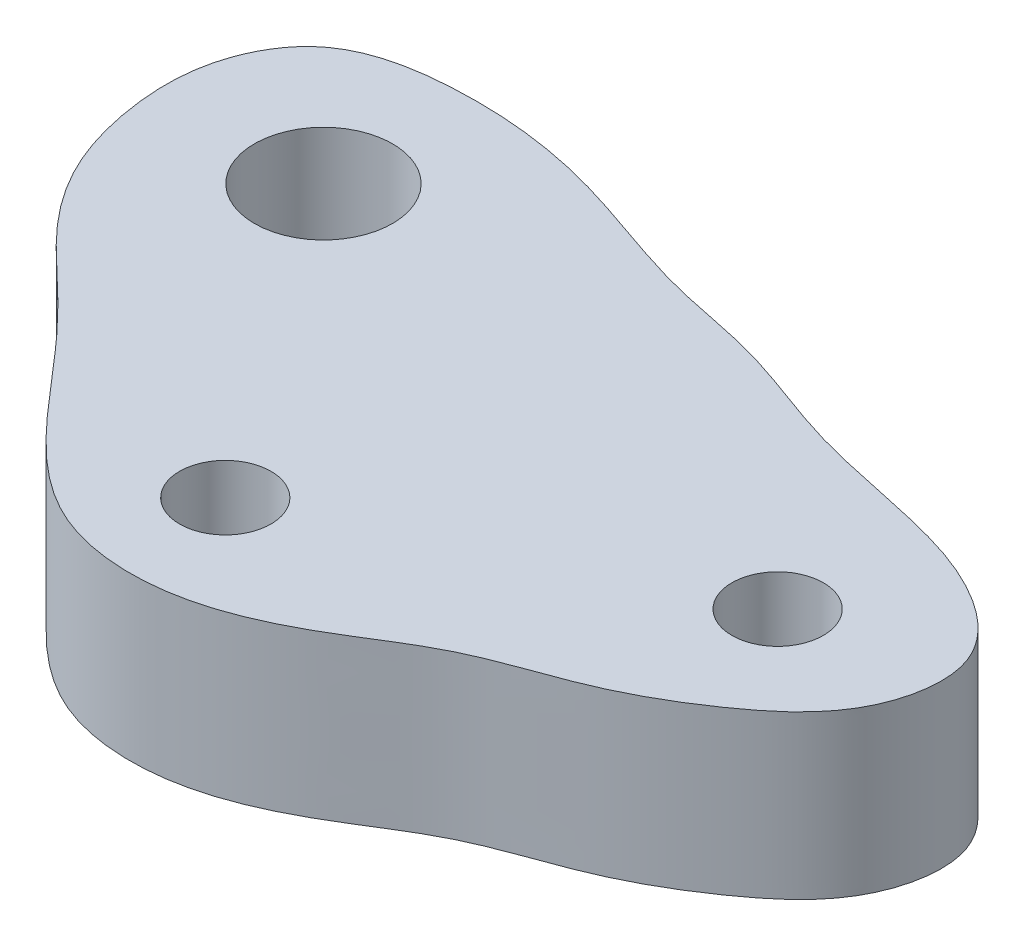
SolidWorks part; units mm, degrees
ref_plane "Front Plane" through (0, 0, 0) normal (0, 0, 1) x (1, 0, 0)
ref_plane "Top Plane" through (0, 0, 0) normal (0, 1, 0) x (1, 0, 0)
ref_plane "Right Plane" through (0, 0, 0) normal (1, 0, 0) x (0, 0, -1)
sketch "Sketch1" plane through (0, 0, 0) normal (0, 1, 0) x (1, 0, 0)
  line L0 (47.2297, 219.0186) -> (732.563, 219.0186) construction
  circle A0 centre (-75.864, 44.3038) radius 1.7
  circle A1 centre (-61.2085, 40.8247) radius 1.125
  circle A2 centre (-70.3795, 36.4027) radius 1.125
  spline S0 degree 3 poles (-75.6424, 37.5341) (-74.1816, 35.7267) (-72.0659, 33.6822) (-68.8977, 33.4714) (-66.3987, 34.5969) (-64.2645, 36.0948) (-61.8442, 36.7908) (-59.6978, 38.0334) (-57.8458, 39.6029) (-57.3741, 42.2609) (-59.306, 43.7346) (-61.6489, 44.4819) (-64.3051, 44.8796) (-66.8643, 46.0171) (-69.7083, 46.4307) (-72.6521, 47.6938) (-75.9085, 48.1123) (-78.8818, 47.595) (-79.9744, 45.4963) (-79.9241, 43.5469) (-79.3846, 41.6321) (-78.2701, 40.0554) (-76.9655, 38.8872) (-75.6424, 37.5341) (-74.1816, 35.7267) (-72.0659, 33.6822) knots -0.099679 -0.067807 -0.041691 0 0.056083 0.106669 0.156386 0.198718 0.243599 0.287767 0.329348 0.369066 0.410029 0.442664 0.500846 0.550164 0.589407 0.651753 0.717087 0.764391 0.796651 0.831998 0.865805 0.900321 0.932193 0.958309 1 1.056083 1.106669 1.156386 only from (-74.3074, 35.951) to (-74.3074, 35.951)
extrude "Boss-Extrude3" add sketch "Sketch1" along normal blind 4
